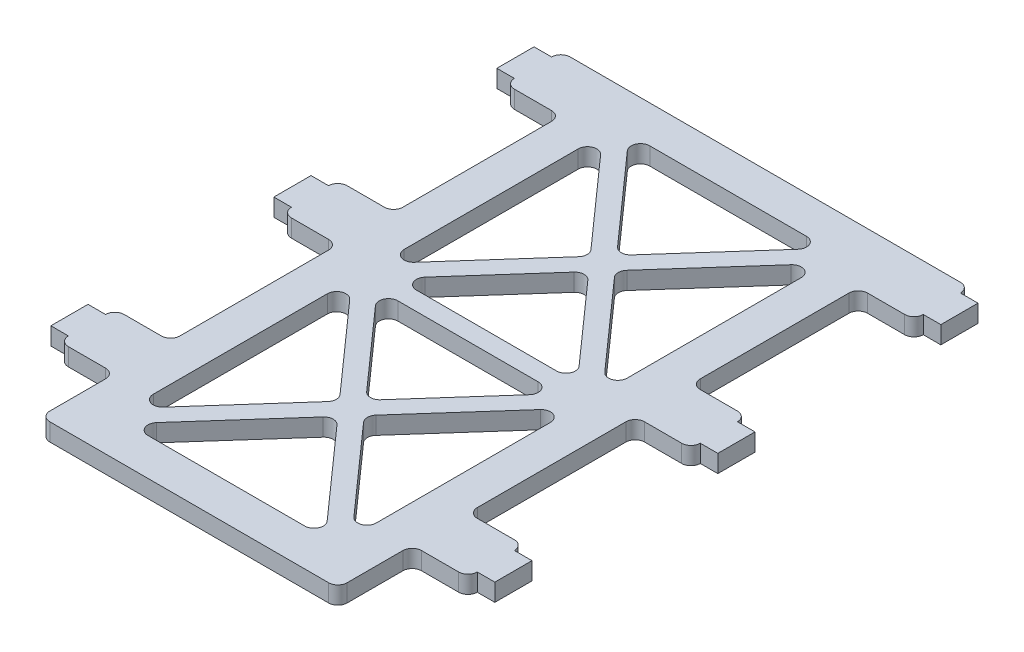
SolidWorks part; units mm, degrees
ref_plane "Front Plane" through (0, 0, 0) normal (0, 0, 1) x (1, 0, 0)
ref_plane "Top Plane" through (0, 0, 0) normal (0, 1, 0) x (1, 0, 0)
ref_plane "Right Plane" through (0, 0, 0) normal (1, 0, 0) x (0, 0, -1)
sketch "Sketch1" plane through (0, 34.29, 0) normal (0, 1, 0) x (1, 0, 0)
  line L0 (28.7528, 184.15) -> (31.75, 184.15) construction
  line L1 (0, -190.5) -> (0, 187.198) construction
  line L2 (38.1028, 187.198) -> (35.1028, 187.198) construction
  line L3 (35.1028, -190.5) -> (38.1, -190.5) construction
  line L5 (-25.4, 71.4375) -> (25.4, 71.4375)
  line L6 (-25.4, 71.4375) -> (-25.4, 169.8625)
  line L7 (-25.4, 169.8625) -> (25.4, 169.8625)
  line L8 (25.4, 71.4375) -> (25.4, 169.8625)
  line L9 (-25.4, 71.4375) -> (25.4, 169.8625) construction
  line L10 (-25.4, 169.8625) -> (25.4, 71.4375) construction
  point P0 (0, 120.65)
  dimension "D1" = 98.425
  dimension "D2" = 50.8
  dimension "D3" = 14.2875
extrude "Boss-Extrude1" add sketch "Sketch1" along normal mid plane 3 contours L7 L8 L5 L6
sketch "Sketch2" plane through (0, 35.79, 0) normal (0, 1, 0) x (1, 0, 0)
  line L0 (0, 169.8625) -> (0, 65.0186) construction
  line L1 (-25.4, 169.8625) -> (25.4, 169.8625) construction
  line L2 (25.4, 127) -> (-25.4, 127) construction
  line L5 (-34.925, 169.8625) -> (-25.4, 160.3375) construction
  line L6 (34.925, 160.3375) -> (25.4, 160.3375)
  line L7 (34.925, 160.3375) -> (34.925, 169.8625)
  line L8 (34.925, 169.8625) -> (25.4, 169.8625)
  line L9 (25.4, 160.3375) -> (25.4, 169.8625)
  line L10 (34.925, 160.3375) -> (25.4, 169.8625) construction
  line L11 (34.925, 169.8625) -> (25.4, 160.3375) construction
  line L12 (-34.925, 160.3375) -> (-25.4, 169.8625) construction
  line L13 (-25.4, 160.3375) -> (-25.4, 169.8625)
  line L14 (-34.925, 169.8625) -> (-25.4, 169.8625)
  line L15 (-34.925, 160.3375) -> (-34.925, 169.8625)
  line L16 (-34.925, 160.3375) -> (-25.4, 160.3375)
  line L17 (34.925, 122.2375) -> (25.4, 122.2375)
  line L18 (34.925, 122.2375) -> (34.925, 131.7625)
  line L19 (34.925, 131.7625) -> (25.4, 131.7625)
  line L20 (25.4, 122.2375) -> (25.4, 131.7625)
  line L21 (34.925, 122.2375) -> (25.4, 131.7625) construction
  line L22 (34.925, 131.7625) -> (25.4, 122.2375) construction
  line L23 (-25.4, 122.2375) -> (-25.4, 131.7625)
  line L24 (-34.925, 131.7625) -> (-25.4, 131.7625)
  line L25 (-34.925, 122.2375) -> (-34.925, 131.7625)
  line L26 (-34.925, 122.2375) -> (-25.4, 122.2375)
  line L27 (-34.925, 131.7625) -> (-25.4, 122.2375) construction
  line L28 (-34.925, 122.2375) -> (-25.4, 131.7625) construction
  line L29 (34.925, 84.1375) -> (25.4, 84.1375)
  line L30 (34.925, 84.1375) -> (34.925, 93.6625)
  line L31 (34.925, 93.6625) -> (25.4, 93.6625)
  line L32 (25.4, 84.1375) -> (25.4, 93.6625)
  line L33 (34.925, 84.1375) -> (25.4, 93.6625) construction
  line L34 (34.925, 93.6625) -> (25.4, 84.1375) construction
  line L35 (-25.4, 84.1375) -> (-25.4, 93.6625)
  line L36 (-34.925, 93.6625) -> (-25.4, 93.6625)
  line L37 (-34.925, 84.1375) -> (-34.925, 93.6625)
  line L38 (-34.925, 84.1375) -> (-25.4, 84.1375)
  line L39 (-34.925, 93.6625) -> (-25.4, 84.1375) construction
  line L40 (-34.925, 84.1375) -> (-25.4, 93.6625) construction
  point P11 (30.1625, 165.1)
  point P21 (-30.1625, 165.1)
  point P24 (30.1625, 127)
  point P33 (-30.1625, 127)
  point P34 (30.1625, 88.9)
  point P43 (-30.1625, 88.9)
  dimension "D1" = 9.525
  dimension "D2" = 9.525
  dimension "D4" = 38.1
  dimension "D3" = 3
extrude "Boss-Extrude2" add sketch "Sketch2" against normal up to surface (3 mm away) up to face at (0, 32.79, -120.65)
sketch "Sketch4" plane through (0, 35.79, 0) normal (0, 1, 0) x (1, 0, 0)
  line L0 (25.4, 131.7625) -> (25.4, 160.3375) construction
  line L1 (-19.05, 163.5125) -> (19.05, 163.5125)
  line L2 (-19.05, 163.5125) -> (-19.05, 77.7875)
  line L3 (-19.05, 77.7875) -> (19.05, 77.7875)
  line L4 (19.05, 163.5125) -> (19.05, 77.7875)
  line L5 (-19.05, 163.5125) -> (19.05, 77.7875) construction
  line L6 (-19.05, 77.7875) -> (19.05, 163.5125) construction
  line L7 (-25.4, 131.7625) -> (-25.4, 160.3375) construction
  line L8 (-34.925, 169.8625) -> (34.925, 169.8625) construction
  line L9 (-25.4, 71.4375) -> (25.4, 71.4375) construction
  line L10 (-19.05, 120.65) -> (19.05, 120.65) construction
  line L11 (19.05, 120.65) -> (-19.05, 163.5125) construction
  line L12 (19.05, 120.65) -> (-19.05, 77.7875) construction
  line L13 (-19.05, 120.65) -> (19.05, 163.5125) construction
  line L14 (19.05, 77.7875) -> (-19.05, 120.65) construction
  line L15 (-19.05, 119.0625) -> (19.05, 119.0625)
  line L16 (-19.05, 122.2375) -> (19.05, 122.2375)
  line L17 (20.2365, 78.8422) -> (-16.926, 120.65)
  line L18 (-16.926, 120.65) -> (20.2365, 162.4578)
  line L19 (21.174, 120.65) -> (-17.8635, 76.7328)
  line L20 (21.174, 120.65) -> (-17.8635, 164.5672)
  line L21 (17.8635, 76.7328) -> (-21.174, 120.65)
  line L22 (-21.174, 120.65) -> (17.8635, 164.5672)
  line L23 (16.926, 120.65) -> (-20.2365, 78.8422)
  line L24 (16.926, 120.65) -> (-20.2365, 162.4578)
  point P0 (0, 120.65)
  dimension "D1" = 6.35
  dimension "D2" = 6.35
  dimension "D3" = 6.35
  dimension "D4" = 6.35
  dimension "D5" = 1.5875
  dimension "D6" = 1.5875
  dimension "D7" = 1.5875
  dimension "D8" = 1.5875
extrude "Cut-Extrude1" cut sketch "Sketch4" against normal blind 3 contours L15 L19 L17 L4 | L3 L21 L19 | L23 L21 L15 L2 | L23 L15 L17 | L16 L24 L18 | L20 L16 L4 L18 | L20 L22 L1 | L22 L24 L2 L16
fillet "Fillet1" radius 1.5875 48 edges at (-15.5149, 34.29, -119.0625) (15.5149, 34.29, -119.0625) (0, 34.29, -101.6083) (-19.05, 34.29, -118.2605) (-2.124, 34.29, -99.2187) (-19.05, 34.29, -80.177) (19.05, 34.29, -161.123) (19.05, 34.29, -123.0395) (2.124, 34.29, -142.0813) (16.926, 34.29, -163.5125) (0, 34.29, -144.4708) (-16.926, 34.29, -163.5125) (2.124, 34.29, -99.2187) (19.05, 34.29, -118.2605) (19.05, 34.29, -80.177) (34.925, 34.29, -84.1375) (34.925, 34.29, -93.6625) (25.4, 34.29, -93.6625) (25.4, 34.29, -122.2375) (34.925, 34.29, -122.2375) (34.925, 34.29, -131.7625) (25.4, 34.29, -131.7625) (25.4, 34.29, -160.3375) (34.925, 34.29, -160.3375) (34.925, 34.29, -169.8625) (-34.925, 34.29, -160.3375) (-25.4, 34.29, -160.3375) (-25.4, 34.29, -131.7625) (-34.925, 34.29, -131.7625) (-34.925, 34.29, -122.2375) (-25.4, 34.29, -122.2375) (-25.4, 34.29, -93.6625) (-34.925, 34.29, -93.6625) (-19.05, 34.29, -123.0395) (-19.05, 34.29, -161.123) (-2.124, 34.29, -142.0813) (-16.926, 34.29, -77.7875) (0, 34.29, -96.8292) (16.926, 34.29, -77.7875) (-15.5149, 34.29, -122.2375) (0, 34.29, -139.6917) (15.5149, 34.29, -122.2375) (-34.925, 34.29, -169.8625) (-25.4, 34.29, -71.4375) (25.4, 34.29, -71.4375) (25.4, 34.29, -84.1375) (-34.925, 34.29, -84.1375) (-25.4, 34.29, -84.1375)
sketch "Sketch5" plane through (0, 35.79, 0) normal (0, 1, 0) x (1, 0, 0)
  line L0 (34.925, 161.925) -> (34.925, 168.275) construction
  line L1 (37.925, 161.925) -> (34.925, 161.925)
  line L2 (37.925, 161.925) -> (37.925, 168.275)
  line L3 (37.925, 168.275) -> (34.925, 168.275)
  line L4 (34.925, 161.925) -> (34.925, 168.275)
  line L5 (37.925, 161.925) -> (34.925, 168.275) construction
  line L6 (37.925, 168.275) -> (34.925, 161.925) construction
  line L7 (34.925, 161.925) -> (34.925, 168.275) construction
  line L8 (34.925, 165.1) -> (36.425, 165.1) construction
  line L9 (0, 196.0278) -> (0, 0) construction
  line L10 (-34.925, 165.1) -> (-36.425, 165.1) construction
  line L11 (-37.925, 168.275) -> (-34.925, 161.925) construction
  line L12 (-37.925, 161.925) -> (-34.925, 168.275) construction
  line L13 (-34.925, 161.925) -> (-34.925, 168.275)
  line L14 (-37.925, 168.275) -> (-34.925, 168.275)
  line L15 (-37.925, 161.925) -> (-37.925, 168.275)
  line L16 (-37.925, 161.925) -> (-34.925, 161.925)
  line L17 (37.925, 123.825) -> (34.925, 123.825)
  line L18 (37.925, 123.825) -> (37.925, 130.175)
  line L19 (37.925, 130.175) -> (34.925, 130.175)
  line L20 (34.925, 123.825) -> (34.925, 130.175)
  line L21 (37.925, 123.825) -> (34.925, 130.175) construction
  line L22 (37.925, 130.175) -> (34.925, 123.825) construction
  line L23 (34.925, 127) -> (36.425, 127) construction
  line L24 (-34.925, 123.825) -> (-34.925, 130.175)
  line L25 (-37.925, 130.175) -> (-34.925, 130.175)
  line L26 (-37.925, 123.825) -> (-37.925, 130.175)
  line L27 (-37.925, 123.825) -> (-34.925, 123.825)
  line L28 (-34.925, 127) -> (-36.425, 127) construction
  line L29 (-37.925, 130.175) -> (-34.925, 123.825) construction
  line L30 (-37.925, 123.825) -> (-34.925, 130.175) construction
  line L31 (37.925, 85.725) -> (34.925, 85.725)
  line L32 (37.925, 85.725) -> (37.925, 92.075)
  line L33 (37.925, 92.075) -> (34.925, 92.075)
  line L34 (34.925, 85.725) -> (34.925, 92.075)
  line L35 (37.925, 85.725) -> (34.925, 92.075) construction
  line L36 (37.925, 92.075) -> (34.925, 85.725) construction
  line L37 (34.925, 88.9) -> (36.425, 88.9) construction
  line L38 (-34.925, 85.725) -> (-34.925, 92.075)
  line L39 (-37.925, 92.075) -> (-34.925, 92.075)
  line L40 (-37.925, 85.725) -> (-37.925, 92.075)
  line L41 (-37.925, 85.725) -> (-34.925, 85.725)
  line L42 (-34.925, 88.9) -> (-36.425, 88.9) construction
  line L43 (-37.925, 92.075) -> (-34.925, 85.725) construction
  line L44 (-37.925, 85.725) -> (-34.925, 92.075) construction
  line L45 (-36.425, 165.1) -> (-36.425, 127) construction
  point P0 (36.425, 165.1)
  point P7 (36.425, 127)
  point P21 (-36.425, 165.1)
  point P35 (-36.425, 127)
  point P36 (36.425, 88.9)
  point P49 (-36.425, 88.9)
  dimension "D1" = 3
  dimension "D2" = 6.35
  dimension "D4" = 38.1
  dimension "D3" = 3
extrude "Boss-Extrude3" add sketch "Sketch5" against normal up to surface (3 mm away)
